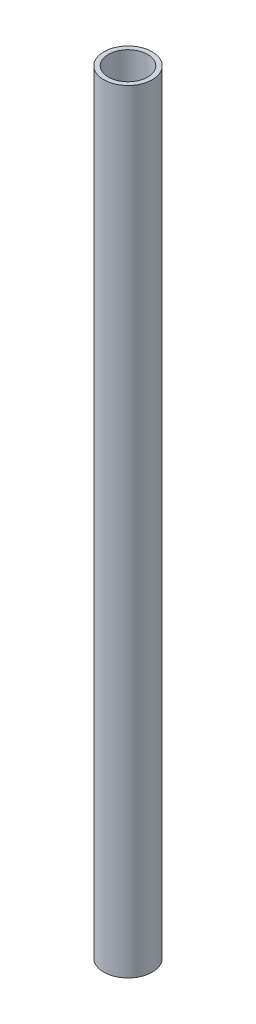
SolidWorks part; units mm, degrees
material "СТ3КП"
ref_plane "Спереди" through (0, 0, 0) normal (0, 0, 1) x (1, 0, 0)
ref_plane "Сверху" through (0, 0, 0) normal (0, 1, 0) x (1, 0, 0)
ref_plane "Справа" through (0, 0, 0) normal (1, 0, 0) x (0, 0, -1)
sketch "Эскиз1" plane through (0, 0, 0) normal (0, 1, 0) x (1, 0, 0)
  line L0 (0, 200839.2922) -> (0, -249082.8193) construction
  line L1 (-130, 9.15) -> (130, 9.15) construction
  circle B0 centre (0, -1.5) radius 8.65
  circle B1 centre (0, -1.5) radius 10.65
sketch_block_instance "Труба 21_3х2 1_2-1"
sketch_block "Труба 21_3х2 1_2" parameters "D2"=21.3, "D1"=2
extrude "Бобышка-Вытянуть1" add sketch "Эскиз1" along normal up to vertex (340 mm away)
